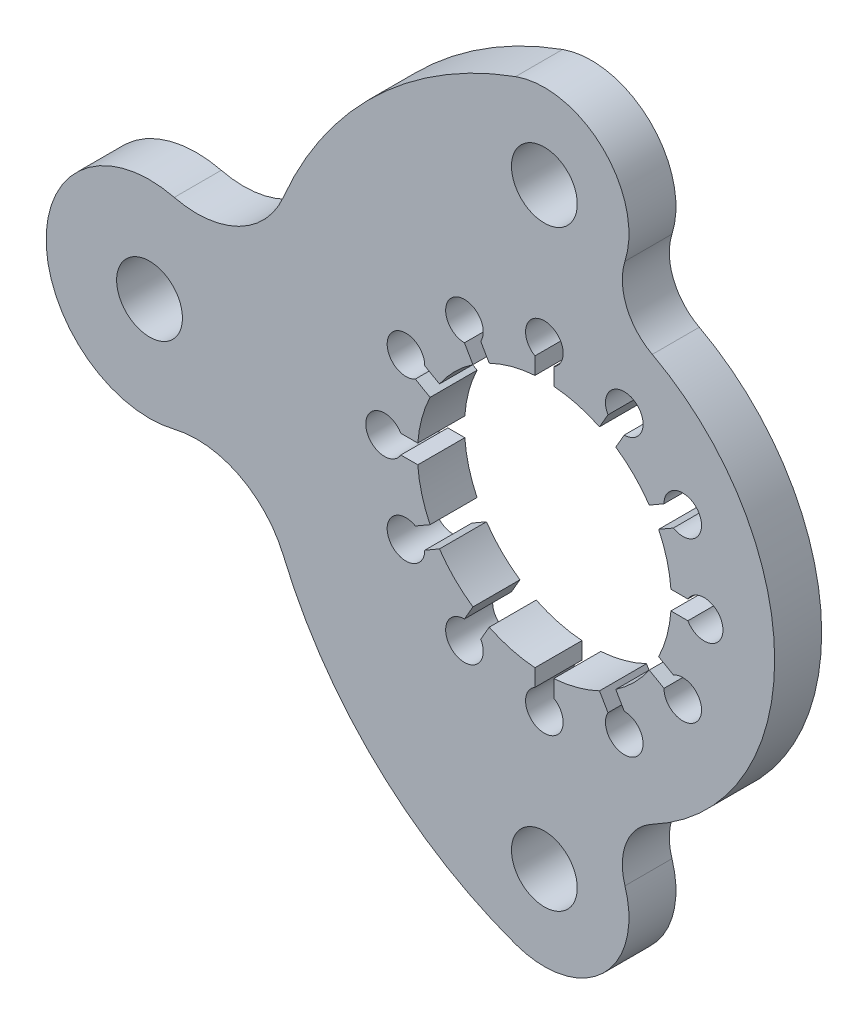
SolidWorks part; units mm, degrees
ref_plane "Alzado" through (0, 0, 0) normal (0, 0, 1) x (1, 0, 0)
ref_plane "Planta" through (0, 0, 0) normal (0, 1, 0) x (1, 0, 0)
ref_plane "Vista lateral" through (0, 0, 0) normal (1, 0, 0) x (0, 0, -1)
sketch "Croquis1" plane through (0, 0, 0) normal (0, 0, 1) x (1, 0, 0)
  line L0 (13.5359, 27.4449) -> (11.7309, 24.3184)
  line L2 (-2, 30.5359) -> (-2, 26.9258)
  line L4 (2, 30.5359) -> (2, 26.9258)
  line L5 (17, 25.4449) -> (15.195, 22.3184)
  line L6 (25.4449, 17) -> (22.3184, 15.195)
  line L7 (27.4449, 13.5359) -> (24.3184, 11.7309)
  line L8 (30.5359, 2) -> (26.9258, 2)
  line L9 (30.5359, -2) -> (26.9258, -2)
  line L10 (27.4449, -13.5359) -> (24.3184, -11.7309)
  line L11 (25.4449, -17) -> (22.3184, -15.195)
  line L12 (17, -25.4449) -> (15.195, -22.3184)
  line L13 (13.5359, -27.4449) -> (11.7309, -24.3184)
  line L14 (2, -30.5359) -> (2, -26.9258)
  line L15 (-2, -30.5359) -> (-2, -26.9258)
  line L16 (-13.5359, -27.4449) -> (-11.7309, -24.3184)
  line L17 (-17, -25.4449) -> (-15.195, -22.3184)
  line L18 (-25.4449, -17) -> (-22.3184, -15.195)
  line L19 (-27.4449, -13.5359) -> (-24.3184, -11.7309)
  line L20 (-30.5359, -2) -> (-26.9258, -2)
  line L21 (-30.5359, 2) -> (-26.9258, 2)
  line L22 (-27.4449, 13.5359) -> (-24.3184, 11.7309)
  line L23 (-25.4449, 17) -> (-22.3184, 15.195)
  line L24 (-17, 25.4449) -> (-15.195, 22.3184)
  line L25 (-13.5359, 27.4449) -> (-11.7309, 24.3184)
  arc A0 (-2, 26.9258) -> (-11.7309, 24.3184) centre (0, 0) ccw
  circle A1 centre (0, 0) radius 34 construction
  circle A2 centre (0, 0) radius 49
  arc A3 (2, 30.5359) -> (-2, 30.5359) centre (0, 34) ccw
  arc A4 (6.9892, 62.6111) -> (-6.9892, 62.6111) centre (0, 0) ccw construction
  circle A5 centre (0, 63) radius 7
  circle A6 centre (0, -63) radius 7
  circle A7 centre (-84, 0) radius 7
  arc A8 (-78.7376, 21.3613) -> (-78.7376, -21.3613) centre (-84, 0) ccw
  arc A9 (17.1498, 57.5333) -> (-6.1263, 79.9254) centre (0, 63) ccw
  arc A10 (-6.1263, -79.9254) -> (17.1498, -57.5333) centre (0, -63) ccw
  arc A11 (17, 25.4449) -> (13.5359, 27.4449) centre (17, 29.4449) ccw
  arc A12 (27.4449, 13.5359) -> (25.4449, 17) centre (29.4449, 17) ccw
  arc A13 (30.5359, -2) -> (30.5359, 2) centre (34, 0) ccw
  arc A14 (25.4449, -17) -> (27.4449, -13.5359) centre (29.4449, -17) ccw
  arc A15 (13.5359, -27.4449) -> (17, -25.4449) centre (17, -29.4449) ccw
  arc A16 (-2, -30.5359) -> (2, -30.5359) centre (0, -34) ccw
  arc A17 (-17, -25.4449) -> (-13.5359, -27.4449) centre (-17, -29.4449) ccw
  arc A18 (-27.4449, -13.5359) -> (-25.4449, -17) centre (-29.4449, -17) ccw
  arc A19 (-30.5359, 2) -> (-30.5359, -2) centre (-34, 0) ccw
  arc A20 (-25.4449, 17) -> (-27.4449, 13.5359) centre (-29.4449, 17) ccw
  arc A21 (-13.5359, 27.4449) -> (-17, 25.4449) centre (-17, 29.4449) ccw
  arc A22 (-15.195, 22.3184) -> (-22.3184, 15.195) centre (0, 0) ccw
  arc A23 (-24.3184, 11.7309) -> (-26.9258, 2) centre (0, 0) ccw
  arc A24 (-26.9258, -2) -> (-24.3184, -11.7309) centre (0, 0) ccw
  arc A25 (-22.3184, -15.195) -> (-15.195, -22.3184) centre (0, 0) ccw
  arc A26 (-11.7309, -24.3184) -> (-2, -26.9258) centre (0, 0) ccw
  arc A27 (2, -26.9258) -> (11.7309, -24.3184) centre (0, 0) ccw
  arc A28 (15.195, -22.3184) -> (22.3184, -15.195) centre (0, 0) ccw
  arc A29 (24.3184, -11.7309) -> (26.9258, -2) centre (0, 0) ccw
  arc A30 (26.9258, 2) -> (24.3184, 11.7309) centre (0, 0) ccw
  arc A31 (22.3184, 15.195) -> (15.195, 22.3184) centre (0, 0) ccw
  arc A32 (11.7309, 24.3184) -> (2, 26.9258) centre (0, 0) ccw
  arc A33 (17.1498, 57.5333) -> (22.9601, 43.2878) centre (28.583, 53.8889) ccw
  arc A34 (22.9601, -43.2878) -> (17.1498, -57.5333) centre (28.583, -53.8889) ccw
  arc A35 (-6.1263, 79.9254) -> (-6.1263, -79.9254) centre (22.8035, 0) ccw
  arc A36 (-55.5236, 33.013) -> (-78.7376, 21.3613) centre (-73.9536, 40.7807) cw
  arc A37 (-78.7376, -21.3613) -> (-55.5236, -33.013) centre (-73.9536, -40.7807) cw
  arc A39 (-6.9892, -62.6111) -> (6.9892, -62.6111) centre (0, 0) ccw construction
  point P78 (0, 0)
  dimension "D1" = 68
  dimension "D2" = 27
  dimension "D3" = 98
  dimension "D4" = 8
  dimension "D5" = 126
  dimension "D6" = 14
  dimension "D7" = 22
  dimension "D8" = 36
  dimension "D12" = 12
  dimension "D13" = 85
  dimension "D14" = 20
  dimension "D9" = 4
  dimension "D11" = 84
  dimension "D10" = 12
extrude "Saliente-Extruir1" add sketch "Croquis1" along normal blind 10 contours A2 A32 L0 A11 L5 A31 L6 A12 L7 A30 L8 A13 L9 A29 L10 A14 L11 A28 L12 A15 L13 A27 L14 A16 L15 A26 L16 A17 L17 A25 L18 A18 L19 A24 L20 A19 L21 A23 L22 A20 L23 A22 L24 A21 L25 A0 L2 A3 L4 | A9 A35 A10 A34 A2 A33 A5 A6 | A8 A37 A35 A36 A7
